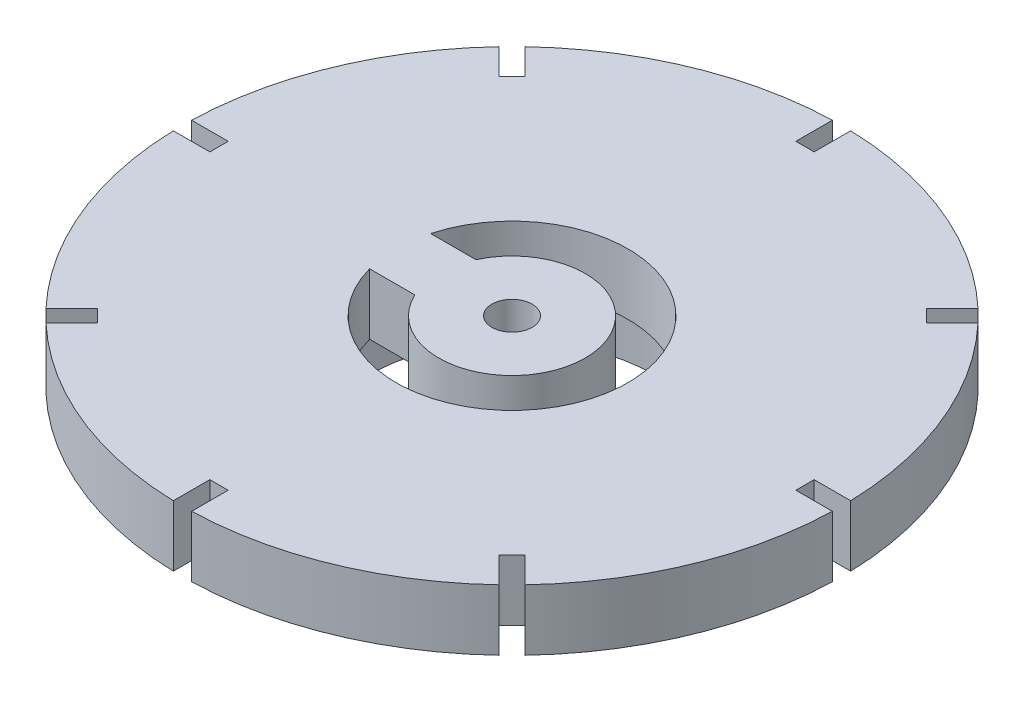
SolidWorks part; units mm, degrees
ref_plane "Front Plane" through (0, 0, 0) normal (0, 0, 1) x (1, 0, 0)
ref_plane "Top Plane" through (0, 0, 0) normal (0, 1, 0) x (1, 0, 0)
ref_plane "Right Plane" through (0, 0, 0) normal (1, 0, 0) x (0, 0, -1)
sketch "Sketch1" plane through (0, 0, 0) normal (0, 1, 0) x (1, 0, 0)
  circle A0 centre (0, 0) radius 15 construction
  circle A1 centre (0, 0) radius 11.65 construction
  arc A2 (0, -11.65) -> (0, 11.65) centre (0, 0) ccw
  arc A3 (0, -15) -> (0, 15) centre (0, 0) ccw
  arc A4 (0, -15) -> (0, 15) centre (0, 0) cw
  arc A5 (0, 11.65) -> (0, -11.65) centre (0, 0) ccw
  dimension "D1" = 30
  dimension "D2" = 23.3
extrude "Boss-Extrude1" add sketch "Sketch1" along normal blind 5
sketch "Sketch2" plane through (0, 5, 0) normal (0, 1, 0) x (1, 0, 0)
  circle A0 centre (0, 0) radius 27
  point P3 (0, 0)
  dimension "D1" = 54
extrude "Boss-Extrude2" add sketch "Sketch2" along normal blind 5
sketch "Sketch3" plane through (0, 5, 0) normal (0, -1, 0) x (1, 0, 0)
  circle A0 centre (0, 0) radius 3
  circle A1 centre (0, 0) radius 5
  dimension "D1" = 6
  dimension "D2" = 10
extrude "Boss-Extrude3" [suppressed] add sketch "Sketch3" along normal blind 1.5
sketch "Sketch4" plane through (0, 5, 0) normal (0, -1, 0) x (1, 0, 0)
  circle A0 centre (0, 0) radius 3
extrude "Cut-Extrude1" cut sketch "Sketch4" against normal offset from surface (2.5 mm away) 2.5 up to face at (0, 10, 27)
sketch "Sketch5" plane through (0, 5, 0) normal (0, -1, 0) x (1, 0, 0)
  line L5 (-9.1652, 2.5) -> (-5.4544, 2.5)
  line L7 (5.5, 0) -> (-5.5, 0) construction
  line L10 (-9.1652, -2.5) -> (-5.4544, -2.5)
  arc A5 (-5.4544, -2.5) -> (-5.4544, 2.5) centre (0, 0) ccw
  arc A6 (-9.1652, -2.5) -> (-9.1652, 2.5) centre (0, 0) ccw
  circle A7 centre (0, 0) radius 3 construction
  dimension "D1" = 3
  dimension "D2" = 3.5
  dimension "D3" = 5
  dimension "D4" = 2.5
extrude "Cut-Extrude2" cut sketch "Sketch5" against normal through all
sketch "Sketch6" plane through (0, 10, 0) normal (0, 1, 0) x (1, 0, 0)
  line L0 (-5.5, 0) -> (5.5, 0) construction
  line L1 (-28.3092, -0.75) -> (-24, -0.75)
  line L2 (-28.3092, -0.75) -> (-28.3092, 0.75)
  line L3 (-28.3092, 0.75) -> (-24, 0.75)
  line L4 (-24, -0.75) -> (-24, 0.75)
  circle A0 centre (0, 0) radius 27 construction
  point P4 (-28.3092, 0)
  point P7 (-23.1822, 0.75)
  point P8 (-28.3092, 0.75)
  dimension "D1" = 1.5
  dimension "D2" = 3
extrude "Cut-Extrude3" cut sketch "Sketch6" against normal through all
pattern_circular "CirPattern1" count 8 over 360 about axis through (0, 0, 0) along (0, 1, 0) of "Cut-Extrude3"
sketch "Sketch7" plane through (0, 10, 0) normal (0, 1, 0) x (1, 0, 0)
  circle A0 centre (0, 0) radius 1.65
  dimension "D1" = 3.3
extrude "Cut-Extrude4" cut sketch "Sketch7" against normal through all
